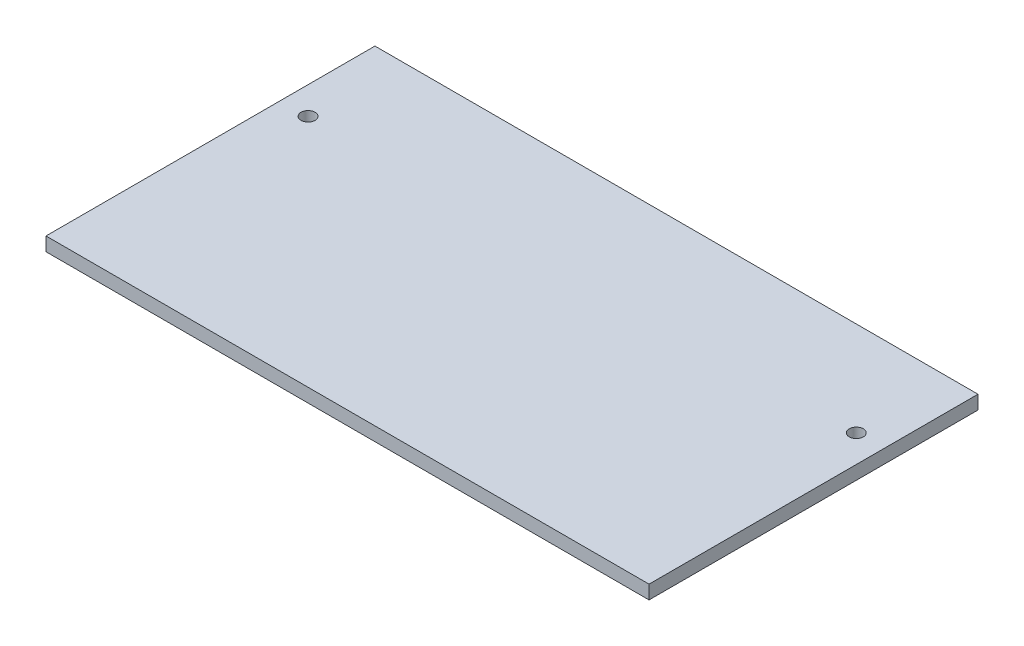
SolidWorks part; units mm, degrees
ref_plane "Front Plane" through (0, 0, 0) normal (0, 0, 1) x (1, 0, 0)
ref_plane "Top Plane" through (0, 0, 0) normal (0, 1, 0) x (1, 0, 0)
ref_plane "Right Plane" through (0, 0, 0) normal (1, 0, 0) x (0, 0, -1)
sketch "Sketch1" plane through (0, 0, 0) normal (0, 1, 0) x (1, 0, 0)
  line L0 (0, 76.2) -> (0, -76.2) construction
  line L1 (-139.7, 76.2) -> (139.7, 76.2)
  line L2 (-139.7, 76.2) -> (-139.7, -76.2)
  line L3 (-139.7, -76.2) -> (139.7, -76.2)
  line L4 (139.7, 76.2) -> (139.7, -76.2)
  line L5 (-139.7, 76.2) -> (139.7, -76.2) construction
  line L6 (-139.7, -76.2) -> (139.7, 76.2) construction
  line L7 (-127, 32.512) -> (0, 32.512) construction
  line L8 (0, 32.512) -> (127, 32.512) construction
  point P4 (0, 0)
  point P5 (-127, 32.512)
  point P9 (127, 32.512)
  dimension "D1" = 152.4
  dimension "D2" = 279.4
  dimension "D3" = 43.688
  dimension "D4" = 127
extrude "Boss-Extrude1" add sketch "Sketch1" along normal blind 6.35
sketch "Sketch4" plane through (0, 6.35, 0) normal (0, 1, 0) x (1, 0, 0)
  point P0 (-127, 32.512)
  point P3 (127, 32.512)
hole_wizard "F (0.257) Diameter Hole1" positions "Sketch4" profile "Sketch3" hole size "F" standard "ANSI Inch" end condition through all
sketch "Sketch3" plane through (-127, 6.35, -32.512) normal (1, 0, 0) x (0, 0, 1)
  line L0 (0, 0) -> (0, 6.35)
  line L1 (0, 6.35) -> (3.2639, 6.35)
  line L2 (3.2639, 6.35) -> (3.2639, 0)
  line L5 (3.2639, 0) -> (0, 0)
  line L11 (0, -6.35) -> (0, 107.95) construction
  dimension "Thru Hole Dia." = 6.5278
  dimension "Thru Hole Depth" = 6.35
